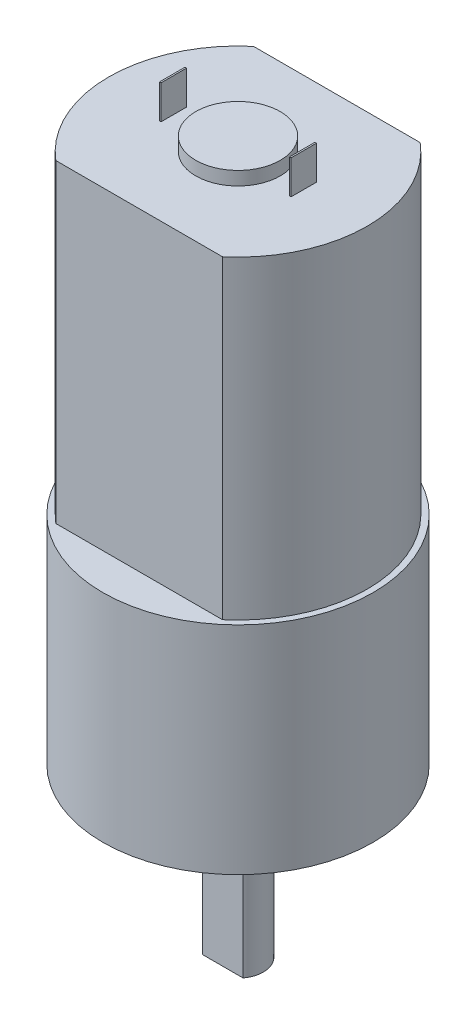
SolidWorks part; units mm, degrees
material "Плата обработки данных, сложная"
ref_plane "Front" through (0, 0, 0) normal (0, 0, 1) x (1, 0, 0)
ref_plane "Top" through (0, 0, 0) normal (0, 1, 0) x (1, 0, 0)
ref_plane "Right" through (0, 0, 0) normal (1, 0, 0) x (0, 0, -1)
sketch "Эскиз1" plane through (0, 0, 0) normal (0, 1, 0) x (1, 0, 0)
  circle A0 centre (0, 0) radius 8
  dimension "D1" = 16
extrude "Бобышка-Вытянуть1" add sketch "Эскиз1" along normal blind 12.8
sketch "Эскиз2" plane through (0, 12.8, 0) normal (0, 1, 0) x (1, 0, 0)
  line L0 (0, 0) -> (13.1985, 0) construction
  line L1 (-4.9295, 5.85) -> (4.9295, 5.85)
  line L2 (-4.9295, -5.85) -> (4.9295, -5.85)
  arc A0 (-4.9295, 5.85) -> (-4.9295, -5.85) centre (0, 0) ccw
  arc A1 (4.9295, -5.85) -> (4.9295, 5.85) centre (0, 0) ccw
  dimension "D1" = 15.3
  dimension "D2" = 11.7
extrude "Бобышка-Вытянуть2" add sketch "Эскиз2" along normal blind 18.6
sketch "Эскиз3" plane through (0, 31.4, 0) normal (0, 1, 0) x (1, 0, 0)
  circle A0 centre (0, 0) radius 2.5
  dimension "D1" = 5
extrude "Бобышка-Вытянуть3" add sketch "Эскиз3" along normal blind 0.8
sketch "Эскиз4" plane through (0, 31.4, 0) normal (0, 1, 0) x (1, 0, 0)
  line L0 (0, 0) -> (0, 8.5407) construction
  line L1 (0, 0) -> (10.0175, 0) construction
  line L2 (-3.8913, 0.75) -> (-3.8913, -0.75)
  line L3 (3.8, 0.75) -> (3.8913, 0.75)
  line L4 (3.8, 0.75) -> (3.8, -0.75)
  line L5 (3.8, -0.75) -> (3.8913, -0.75)
  line L6 (3.8913, 0.75) -> (3.8913, -0.75)
  line L7 (-3.8, -0.75) -> (-3.8913, -0.75)
  line L8 (-3.8, 0.75) -> (-3.8, -0.75)
  line L9 (-3.8, 0.75) -> (-3.8913, 0.75)
  dimension "D1" = 1.5
  dimension "D2" = 0.75
  dimension "D3" = 3.8
extrude "Бобышка-Вытянуть4" add sketch "Эскиз4" along normal blind 2
sketch "Эскиз5" plane through (0, 0, 0) normal (0, -1, 0) x (1, 0, 0)
  circle A0 centre (0, 0) radius 3
  dimension "D1" = 6
extrude "Бобышка-Вытянуть5" add sketch "Эскиз5" along normal blind 2.3
sketch "Эскиз6" plane through (0, -2.3, 0) normal (0, -1, 0) x (1, 0, 0)
  line L0 (0, 0) -> (0, 4.1021) construction
  line L1 (-1.2, 0.9) -> (1.2, 0.9)
  line L2 (-1.55, -1.5) -> (3.8718, -1.5) construction
  line L3 (0, 0) -> (3.8718, 0) construction
  arc A0 (-1.2, 0.9) -> (1.2, 0.9) centre (0, 0) ccw
  dimension "D1" = 3
  dimension "D2" = 1.5
  dimension "D3" = 2.4
extrude "Бобышка-Вытянуть6" add sketch "Эскиз6" along normal blind 7.6
